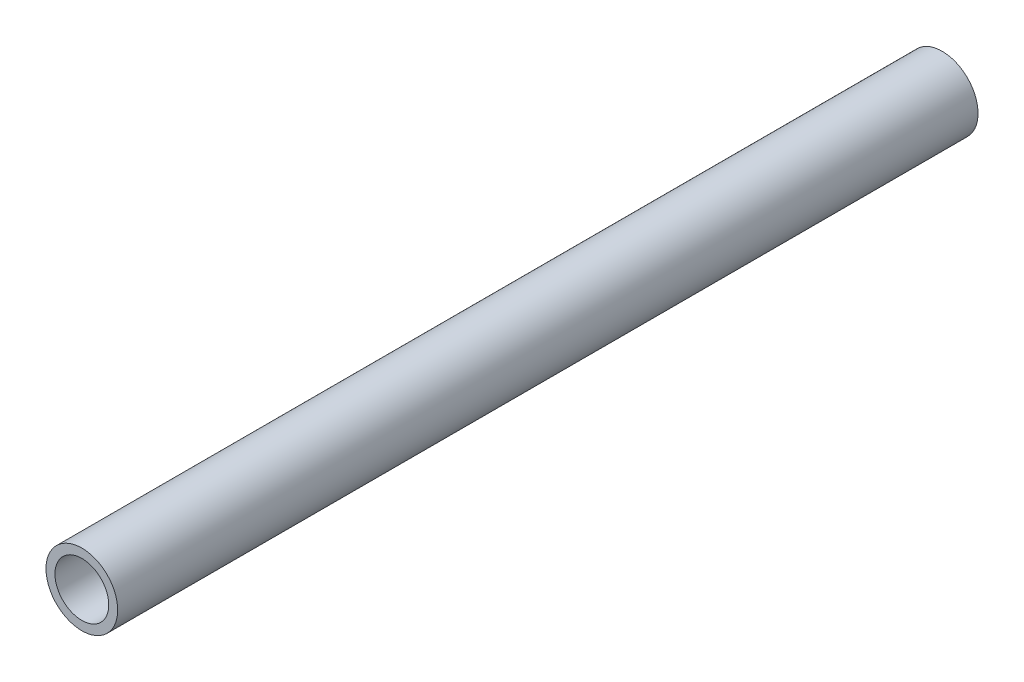
SolidWorks part; units mm, degrees
ref_plane "Front Plane" through (0, 0, 0) normal (0, 0, 1) x (1, 0, 0)
ref_plane "Top Plane" through (0, 0, 0) normal (0, 1, 0) x (1, 0, 0)
ref_plane "Right Plane" through (0, 0, 0) normal (1, 0, 0) x (0, 0, -1)
sketch "Sketch1" plane through (0, 0, 0) normal (0, 0, 1) x (1, 0, 0)
  circle A0 centre (0, 0) radius 6.35
  circle A1 centre (0, 0) radius 4.7625
  dimension "D1" = 12.7
  dimension "D2" = 9.525
extrude "Boss-Extrude1" add sketch "Sketch1" along normal blind 152.4
ref_plane "Plane1" through (6.35, 0, 0) normal (1, 0, 0) x (0, 0, -1)
sketch "Sketch2" plane through (0, 0, 0) normal (0, 0, -1) x (-1, 0, 0)
  line L0 (-6.35, 6.35) -> (-6.35, -6.35) construction
  line L1 (-6.35, 6.985) -> (-6.35, -6.985) construction
  dimension "D1" = 6.35
  dimension "D2" = 12.7
